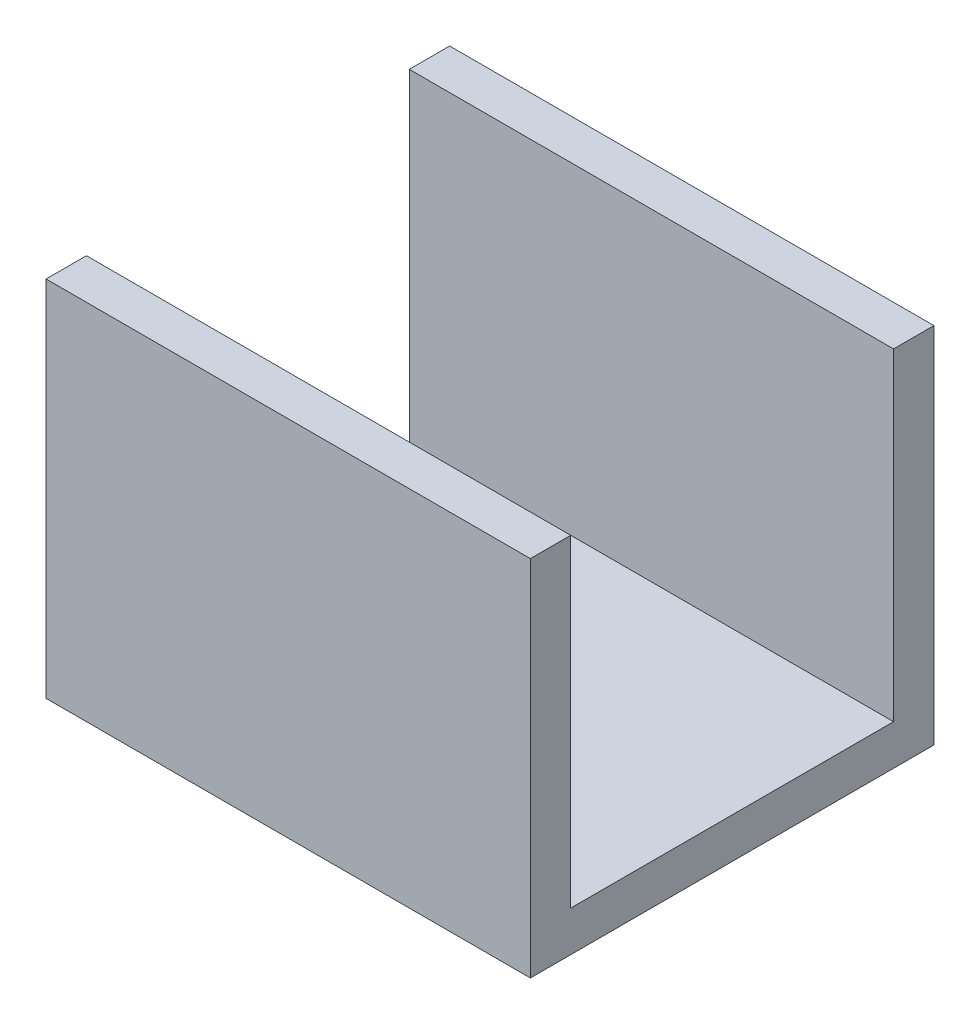
SolidWorks part; units mm, degrees
ref_plane "Front Plane" through (0, 0, 0) normal (0, 0, 1) x (1, 0, 0)
ref_plane "Top Plane" through (0, 0, 0) normal (0, 1, 0) x (1, 0, 0)
ref_plane "Right Plane" through (0, 0, 0) normal (1, 0, 0) x (0, 0, -1)
sketch "Sketch1" plane through (0, 0, 0) normal (0, 1, 0) x (1, 0, 0)
  line L1 (-38.1, -31.75) -> (38.1, -31.75)
  line L2 (-38.1, -31.75) -> (-38.1, 31.75)
  line L3 (-38.1, 31.75) -> (38.1, 31.75)
  line L4 (38.1, -31.75) -> (38.1, 31.75)
  line L5 (-38.1, -31.75) -> (38.1, 31.75) construction
  line L6 (-38.1, 31.75) -> (38.1, -31.75) construction
  point P0 (0, 0)
  dimension "D1" = 76.2
  dimension "D2" = 63.5
extrude "Boss-Extrude1" add sketch "Sketch1" along normal blind 6.35
sketch "Sketch2" plane through (0, 6.35, 0) normal (0, 1, 0) x (1, 0, 0)
  line L0 (38.1, -31.75) -> (38.1, 31.75) construction
  line L1 (-38.1, 31.75) -> (38.1, 31.75)
  line L2 (-38.1, 31.75) -> (-38.1, 25.4)
  line L3 (-38.1, 25.4) -> (38.1, 25.4)
  line L4 (38.1, 31.75) -> (38.1, 25.4)
  line L5 (-38.1, 31.75) -> (-38.1, -31.75) construction
  line L6 (-38.1, -25.4) -> (38.1, -25.4)
  line L7 (-38.1, -25.4) -> (-38.1, -31.75)
  line L8 (-38.1, -31.75) -> (38.1, -31.75)
  line L9 (38.1, -25.4) -> (38.1, -31.75)
  dimension "D1" = 6.35
  dimension "D2" = 6.35
extrude "Boss-Extrude2" add sketch "Sketch2" along normal blind 50.8
sketch "Sketch3" plane through (0, 0, 0) normal (0, -1, 0) x (1, 0, 0)
  circle A0 centre (0, 0) radius 3.175
  dimension "D1" = 6.35
extrude "Boss-Extrude3" add sketch "Sketch3" along normal blind 25.4
